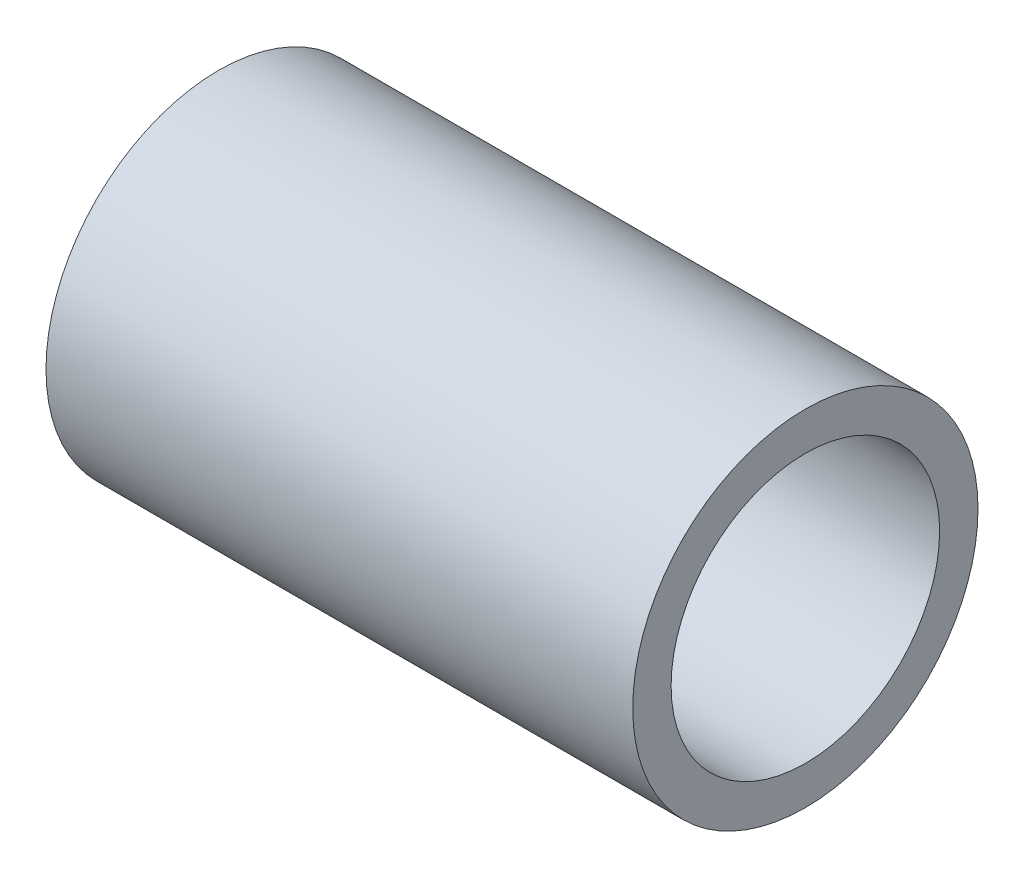
SolidWorks part; units mm, degrees
ref_plane "Front Plane" through (0, 0, 0) normal (0, 0, 1) x (1, 0, 0)
ref_plane "Top Plane" through (0, 0, 0) normal (0, 1, 0) x (1, 0, 0)
ref_plane "Right Plane" through (0, 0, 0) normal (1, 0, 0) x (0, 0, -1)
sketch "Sketch1" plane through (0, 0, 0) normal (0, 0, 1) x (1, 0, 0)
  line L0 (6.35, 14.2875) -> (54.9123, 14.2875)
  line L1 (54.9123, 14.2875) -> (54.9123, 11.1125)
  line L2 (54.9123, 11.1125) -> (16.8123, 11.1125)
  line L3 (16.8123, 11.1125) -> (6.3461, 2.3303)
  line L4 (3.4835, 1.6957) -> (0, 2.6291)
  line L5 (0, 2.6291) -> (0, 4.6037)
  line L6 (0, 0) -> (148.7434, 0) construction
  line L7 (3.335, 1.5875) -> (7.1545, 1.5875) construction
  line L8 (0, 4.6037) -> (6.35, 4.6037)
  line L9 (6.35, 4.6037) -> (6.35, 14.2875)
  arc A0 (6.3461, 2.3303) -> (3.4835, 1.6957) centre (4.3053, 4.7625) cw
  point P11 (5.08, 1.2679)
  dimension "D8" = 3.175
  dimension "D1" = 11.1125
  dimension "D2" = 38.1
  dimension "D3" = 40
  dimension "D4" = 1.5875
  dimension "D5" = 15
  dimension "D6" = 5.08
  dimension "D7" = 3.175
  dimension "D9" = 4.6037
  dimension "D10" = 6.35
revolve "Revolve1" add sketch "Sketch1" angle 360 about L6
